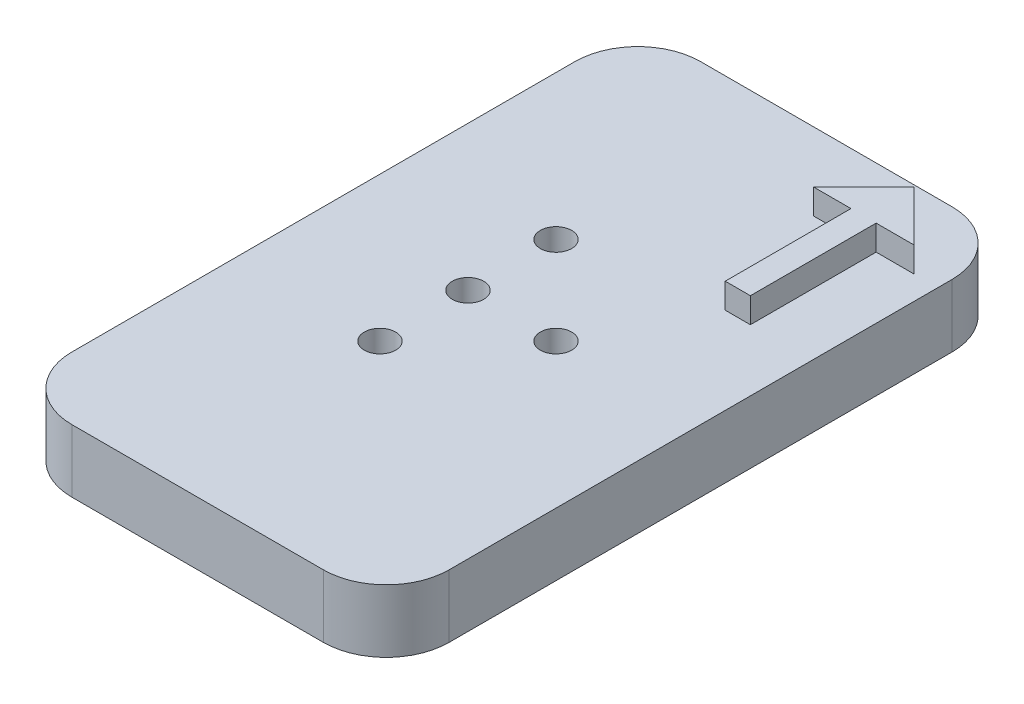
SolidWorks part; units mm, degrees
ref_plane "Front Plane" through (0, 0, 0) normal (0, 0, 1) x (1, 0, 0)
ref_plane "Top Plane" through (0, 0, 0) normal (0, 1, 0) x (1, 0, 0)
ref_plane "Right Plane" through (0, 0, 0) normal (1, 0, 0) x (0, 0, -1)
sketch "Sketch1" plane through (0, 0, 0) normal (0, 1, 0) x (1, 0, 0)
  line L0 (0, 0) -> (0, 7) construction
  line L1 (0, 0) -> (0, -7) construction
  line L2 (0, 0) -> (7, 0) construction
  line L3 (3.5, 2.1389) -> (3.5, -2.1389) construction
  line L4 (-11.5, 25) -> (18.5, 25)
  line L5 (-11.5, 25) -> (-11.5, -25)
  line L6 (-11.5, -25) -> (18.5, -25)
  line L7 (18.5, 25) -> (18.5, -25)
  circle A0 centre (0, 0) radius 1.25
  circle A1 centre (0, 7) radius 1.25
  circle A2 centre (7, 0) radius 1.25
  circle A3 centre (0, -7) radius 1.25
  point P13 (18.5, 0)
  point P16 (3.5, 0)
  point P17 (3.5, -25)
  dimension "D1" = 2.5
  dimension "D2" = 7
  dimension "D3" = 30
  dimension "D4" = 50
extrude "Boss-Extrude1" add sketch "Sketch1" along normal blind 5
fillet "Fillet1" radius 5 4 edges at (-11.5, 2.5, 25) (18.5, 2.5, 25) (18.5, 2.5, -25) (-11.5, 2.5, -25)
sketch "Sketch2" plane through (0, 5, 0) normal (0, 1, 0) x (1, 0, 0)
  line L0 (3.5, 25) -> (3.5, -25) construction
  line L1 (8.6008, 18.8562) -> (16.6008, 18.8562) construction
  line L5 (13.5, 25) -> (-6.5, 25) construction
  line L6 (-6.5, -25) -> (13.5, -25) construction
  line L7 (-11.5, 0) -> (18.5, 0) construction
  line L8 (-11.5, 20) -> (-11.5, -20) construction
  line L9 (18.5, -20) -> (18.5, 20) construction
  line L10 (11.6008, 18.8562) -> (11.6008, 8.8562)
  line L11 (11.6008, 8.8562) -> (13.6008, 8.8562)
  line L12 (13.6008, 8.8562) -> (13.6008, 18.8562)
  line L13 (13.6008, 18.8562) -> (16.6008, 18.8562)
  line L14 (16.6008, 18.8562) -> (12.6008, 22.8562)
  line L15 (12.6008, 22.8562) -> (8.6008, 18.8562)
  line L16 (8.6008, 18.8562) -> (11.6008, 18.8562)
  point P0 (12.6008, 18.8562)
  point P1 (12.6008, 22.8562)
  dimension "D1" = 2
  dimension "D2" = 10
  dimension "D4" = 3
  dimension "D5" = 3
extrude "Boss-Extrude2" add sketch "Sketch2" along normal blind 2
